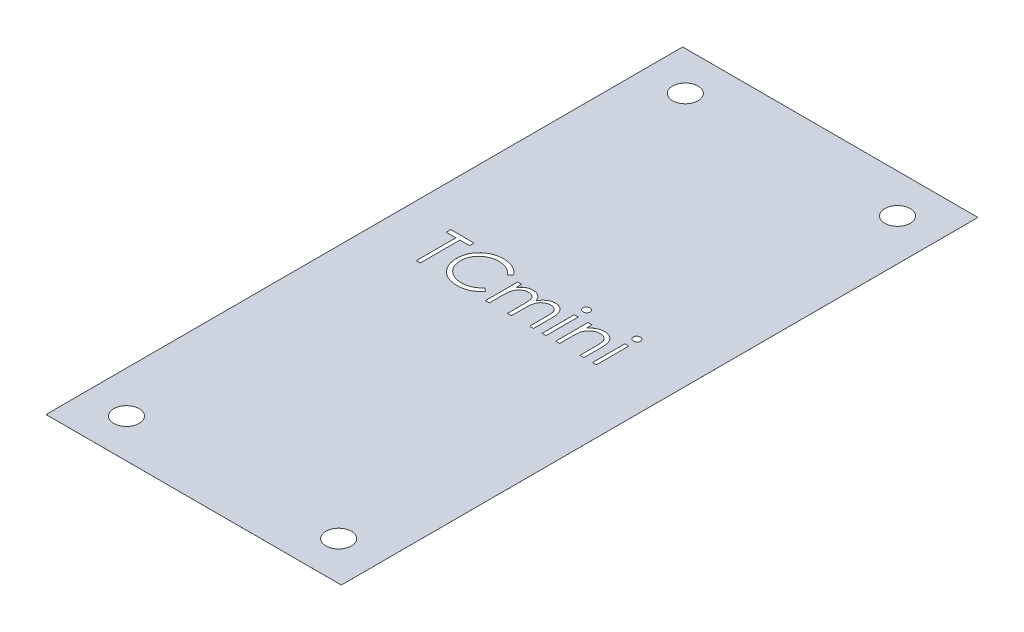
SolidWorks part; units mm, degrees
ref_plane "Front Plane" through (0, 0, 0) normal (0, 0, 1) x (1, 0, 0)
ref_plane "Top Plane" through (0, 0, 0) normal (0, 1, 0) x (1, 0, 0)
ref_plane "Right Plane" through (0, 0, 0) normal (1, 0, 0) x (0, 0, -1)
sketch "Sketch2" plane through (0, 0, 0) normal (0, 1, 0) x (1, 0, 0)
  line L1 (-21.209, -45.72) -> (21.209, -45.72)
  line L2 (-21.209, -45.72) -> (-21.209, 45.72)
  line L3 (-21.209, 45.72) -> (21.209, 45.72)
  line L4 (21.209, -45.72) -> (21.209, 45.72)
  line L5 (-21.209, -45.72) -> (21.209, 45.72) construction
  line L6 (-21.209, 45.72) -> (21.209, -45.72) construction
  point P0 (0, 0)
  dimension "D1" = 91.44
  dimension "D2" = 42.418
extrude "Boss-Extrude1" add sketch "Sketch2" along normal blind 0.0025
sketch "Sketch3" plane through (0, 0.0025, 0) normal (0, 1, 0) x (1, 0, 0)
  line L1 (-15.24, -40.132) -> (15.24, -40.132)
  line L2 (-15.24, -40.132) -> (-15.24, 40.132)
  line L3 (-15.24, 40.132) -> (15.24, 40.132)
  line L4 (15.24, -40.132) -> (15.24, 40.132)
  line L5 (-15.24, -40.132) -> (15.24, 40.132) construction
  line L6 (-15.24, 40.132) -> (15.24, -40.132) construction
  circle A0 centre (-15.24, 40.132) radius 1.8288
  circle A7 centre (15.24, 40.132) radius 1.8288
  circle A8 centre (15.24, -40.132) radius 1.8288
  circle A9 centre (-15.24, -40.132) radius 1.8288
  point P0 (0, 0)
  dimension "D3" = 3.6576
  dimension "D1" = 80.264
  dimension "D2" = 30.48
  dimension "D4" = 2
  dimension "D5" = 2
extrude "Cut-Extrude1" cut sketch "Sketch3" against normal through all contours A9 | A8 | A7 | A0
sketch "Sketch5" plane through (0, 0.0025, 0) normal (0, 1, 0) x (1, 0, 0)
  text T0 "TCmini" font "Century Gothic" height 6.35
extrude "Cut-Extrude2" cut sketch "Sketch5" against normal blind 2.54
